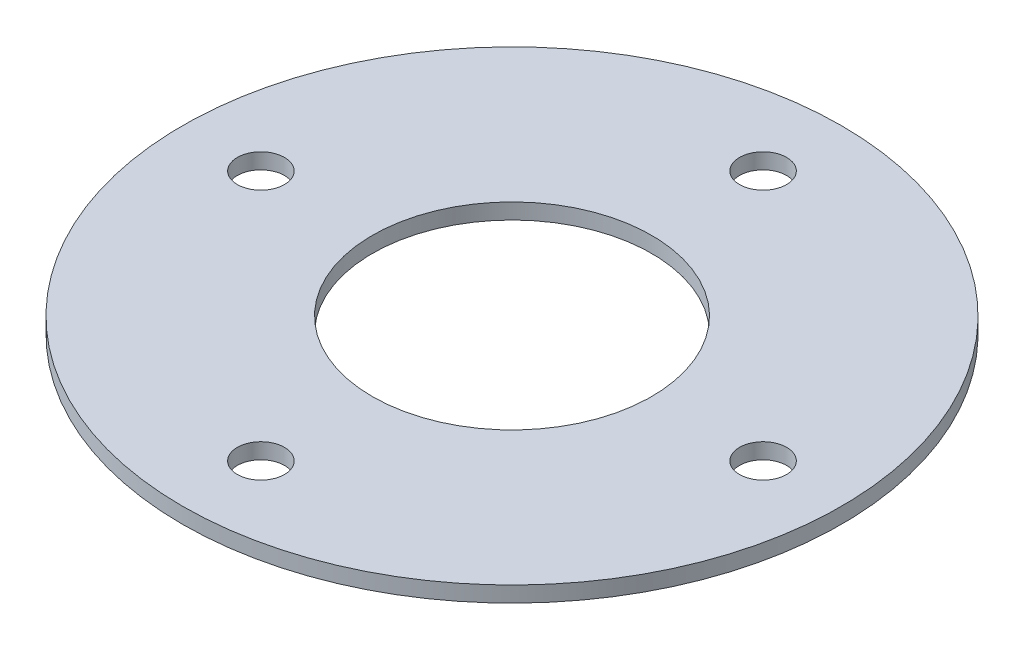
SolidWorks part; units mm, degrees
material "1023 Carbon Steel Sheet (SS)"
ref_plane "Front Plane" through (0, 0, 0) normal (0, 0, 1) x (1, 0, 0)
ref_plane "Top Plane" through (0, 0, 0) normal (0, 1, 0) x (1, 0, 0)
ref_plane "Right Plane" through (0, 0, 0) normal (1, 0, 0) x (0, 0, -1)
sketch "Sketch1" plane through (0, 0, 0) normal (0, 1, 0) x (1, 0, 0)
  circle A0 centre (0, 0) radius 8.9
  circle A1 centre (0, 0) radius 21
  circle A3 centre (0, 16) radius 1.5
  circle A4 centre (16, 0) radius 1.5
  circle A5 centre (0, -16) radius 1.5
  circle A6 centre (-16, 0) radius 1.5
  point P16 (0, 0)
  dimension "D1" = 17.8
  dimension "D2" = 42
  dimension "D4" = 3
  dimension "D5" = 4
extrude "Boss-Extrude1" add sketch "Sketch1" along normal blind 1
